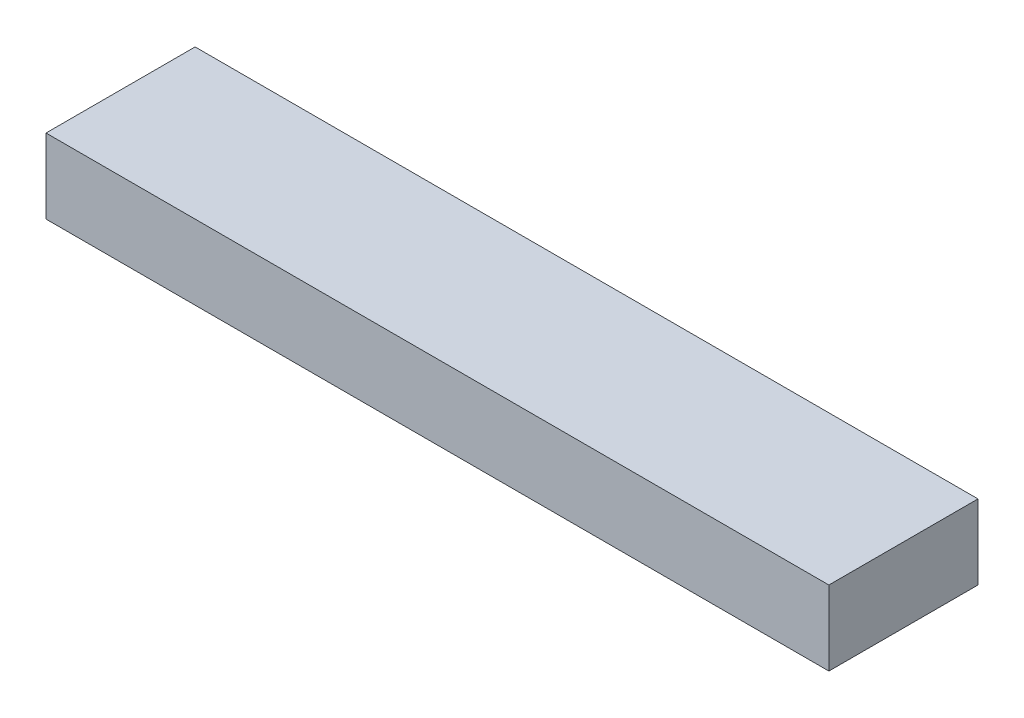
SolidWorks part; units mm, degrees
ref_plane "Plan de face" through (0, 0, 0) normal (0, 0, 1) x (1, 0, 0)
ref_plane "Plan de dessus" through (0, 0, 0) normal (0, 1, 0) x (1, 0, 0)
ref_plane "Plan de droite" through (0, 0, 0) normal (1, 0, 0) x (0, 0, -1)
sketch "Esquisse1" plane through (0, 0, 0) normal (0, 1, 0) x (1, 0, 0)
  line L1 (0.525, -0.1) -> (-0.525, -0.1)
  line L2 (0.525, -0.1) -> (0.525, 0.1)
  line L3 (0.525, 0.1) -> (-0.525, 0.1)
  line L4 (-0.525, -0.1) -> (-0.525, 0.1)
  line L5 (0.525, -0.1) -> (-0.525, 0.1) construction
  line L6 (0.525, 0.1) -> (-0.525, -0.1) construction
  point P0 (0, 0)
  dimension "D1" = 1.05
  dimension "D2" = 0.2
extrude "Boss.-Extru.1" add sketch "Esquisse1" along normal blind 0.1
